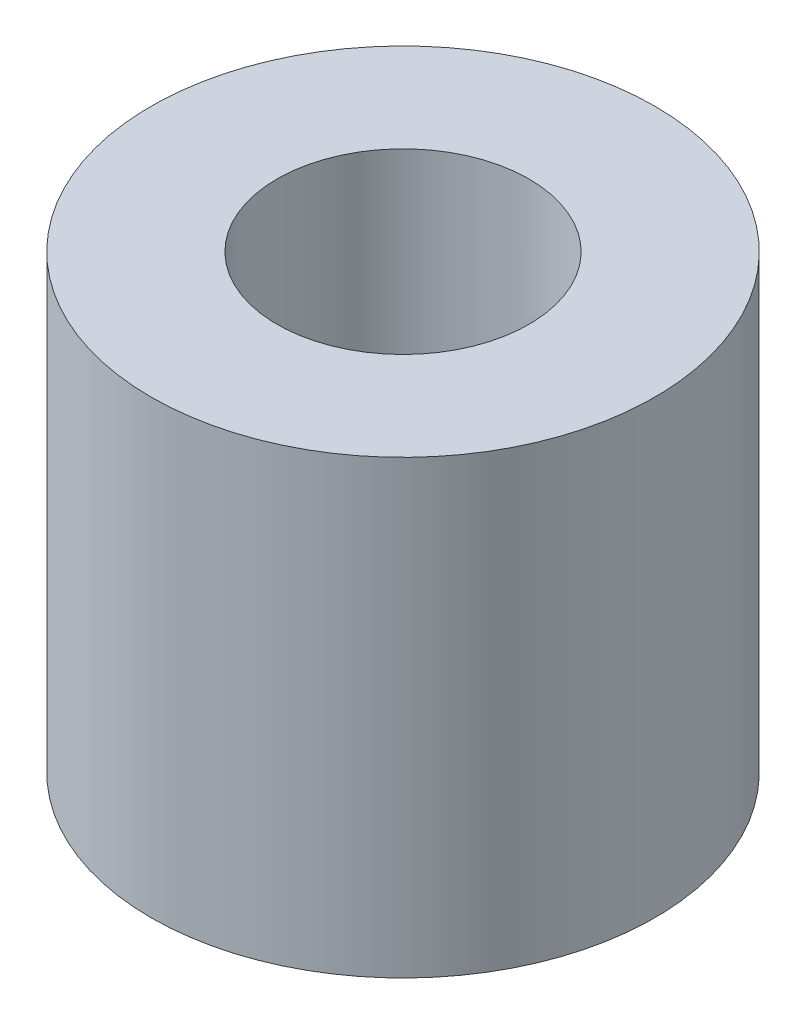
SolidWorks part; units mm, degrees
ref_plane "Спереди" through (0, 0, 0) normal (0, 0, 1) x (1, 0, 0)
ref_plane "Сверху" through (0, 0, 0) normal (0, 1, 0) x (1, 0, 0)
ref_plane "Справа" through (0, 0, 0) normal (1, 0, 0) x (0, 0, -1)
sketch "Эскиз1" plane through (0, 0, 0) normal (0, 1, 0) x (1, 0, 0)
  circle A0 centre (0, 0) radius 3.5
  circle A1 centre (0, 0) radius 7
  dimension "D1" = 7
  dimension "D2" = 14
extrude "Вытянуть1" add sketch "Эскиз1" along normal up to surface (12.53 mm away) from surface at 103.7216
